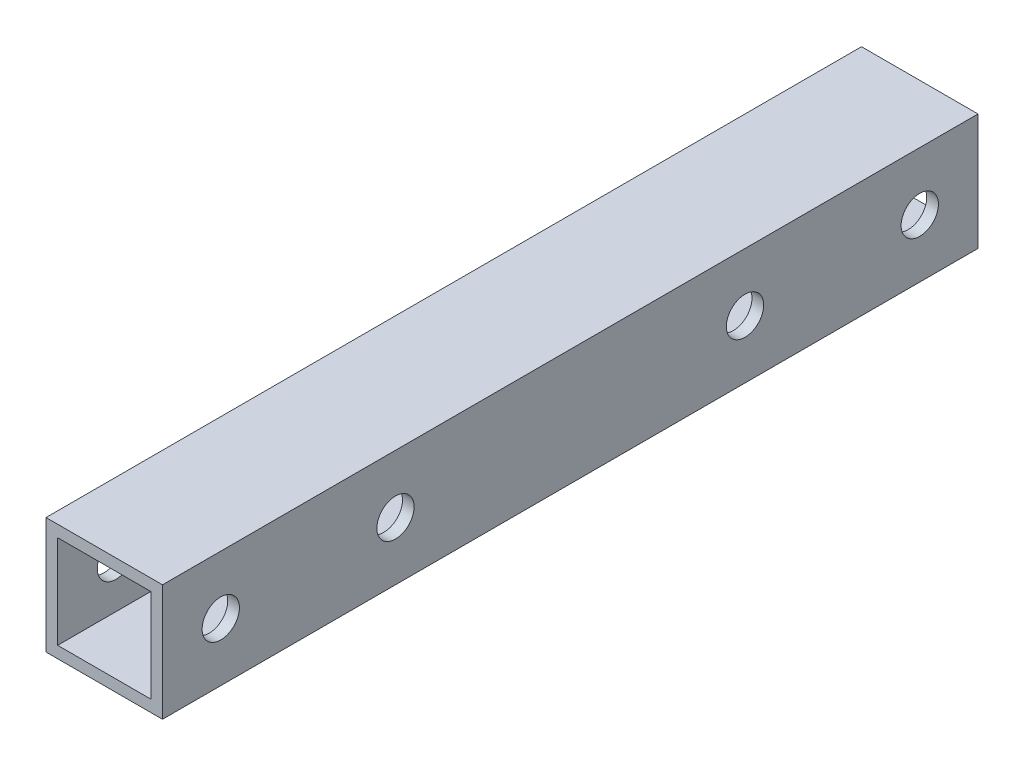
SolidWorks part; units mm, degrees
material "1060 合金"
ref_plane "正面" through (0, 0, 0) normal (0, 0, 1) x (1, 0, 0)
ref_plane "平面" through (0, 0, 0) normal (0, 1, 0) x (1, 0, 0)
ref_plane "右側面" through (0, 0, 0) normal (1, 0, 0) x (0, 0, -1)
sketch "ｽｹｯﾁ1" plane through (0, 0, 0) normal (0, 0, 1) x (1, 0, 0)
  line L1 (-5, -5) -> (5, -5)
  line L2 (-5, -5) -> (-5, 5)
  line L3 (-5, 5) -> (5, 5)
  line L4 (5, -5) -> (5, 5)
  line L5 (-5, -5) -> (5, 5) construction
  line L6 (-5, 5) -> (5, -5) construction
  point P0 (0, 0)
  dimension "D1" = 10
extrude "押し出し-薄板1" add sketch "ｽｹｯﾁ1" along normal blind 70 thin thin type one direction reverse wall 1
sketch "ｽｹｯﾁ2" plane through (5, 0, 0) normal (1, 0, 0) x (0, 0, -1)
  line L0 (-70, 0) -> (0, 0) construction
  line L1 (-70, -5) -> (-70, 5) construction
  line L2 (0, -5) -> (0, 5) construction
  circle A0 centre (-65, 0) radius 1.6
  circle A1 centre (-5, 0) radius 1.6
  circle A2 centre (-20, 0) radius 1.6
  dimension "D1" = 5
  dimension "D2" = 3.2
  dimension "D3" = 3.2
  dimension "D4" = 5
  dimension "D5" = 3.2
  dimension "D6" = 15
extrude "ｶｯﾄ - 押し出し1" cut sketch "ｽｹｯﾁ2" against normal through all
sketch "ｽｹｯﾁ3" plane through (5, 0, 0) normal (1, 0, 0) x (0, 0, -1)
  line L0 (-70, 0) -> (0, 0) construction
  line L1 (-70, -5) -> (-70, 5) construction
  circle A0 centre (-50, 0) radius 1.6
  circle A1 centre (-65, 0) radius 1.6 construction
  dimension "D1" = 15
extrude "ｶｯﾄ - 押し出し2" cut sketch "ｽｹｯﾁ3" against normal through all
